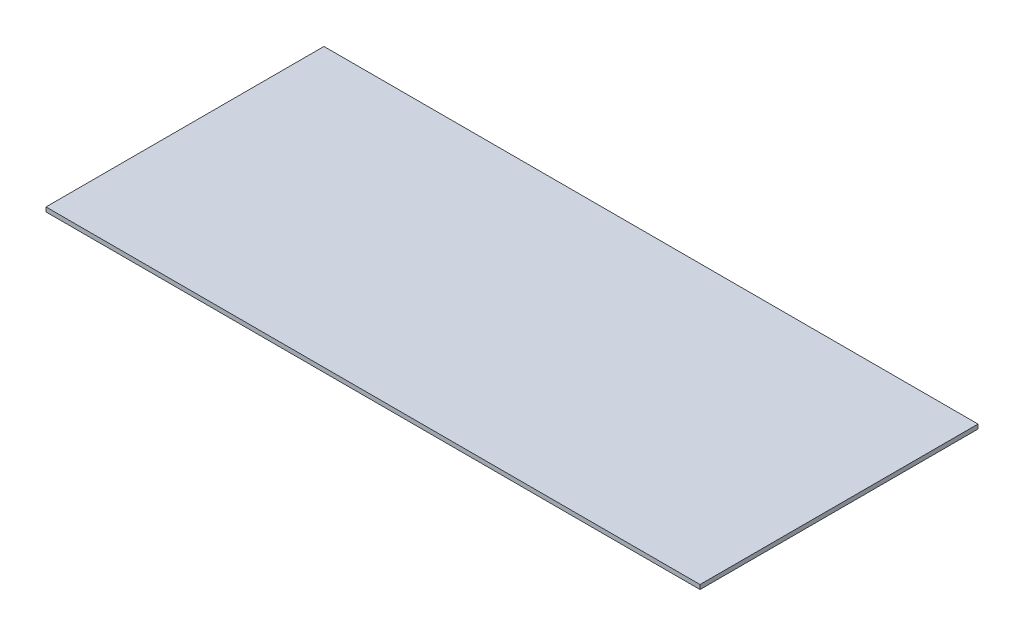
SolidWorks part; units mm, degrees
material "1060 Alloy"
ref_plane "Front" through (0, 0, 0) normal (0, 0, 1) x (1, 0, 0)
ref_plane "Top" through (0, 0, 0) normal (0, 1, 0) x (1, 0, 0)
ref_plane "Right" through (0, 0, 0) normal (1, 0, 0) x (0, 0, -1)
sketch "Sketch1" plane through (0, 0, 0) normal (0, 1, 0) x (1, 0, 0)
  line L1 (0, 0) -> (190.5, 0)
  line L2 (0, 0) -> (0, 80.9625)
  line L3 (0, 80.9625) -> (190.5, 80.9625)
  line L4 (190.5, 0) -> (190.5, 80.9625)
  dimension "D1" = 80.9625
  dimension "D2" = 190.5
extrude "Boss-Extrude1" add sketch "Sketch1" along normal blind 1.27
